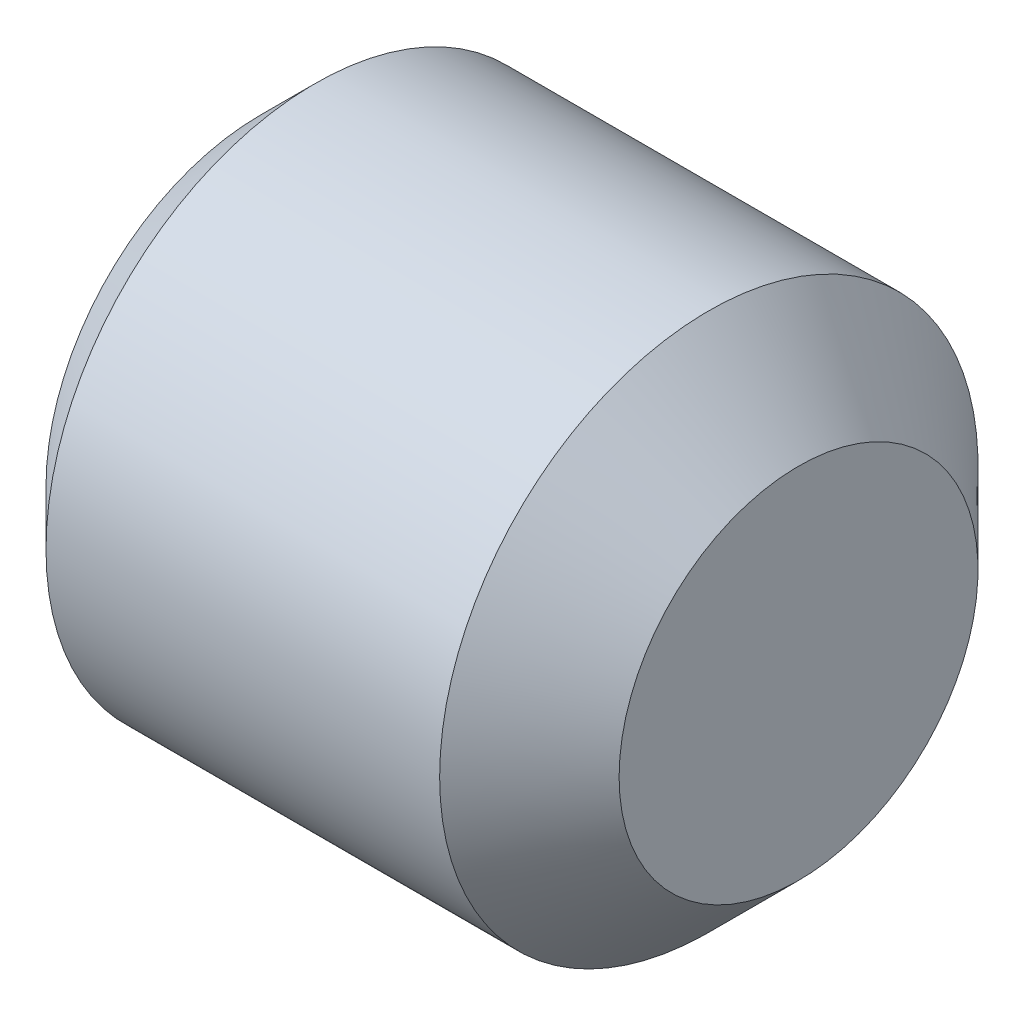
SolidWorks part; units mm, degrees
ref_plane "Front Plane" through (0, 0, 0) normal (0, 0, 1) x (1, 0, 0)
ref_plane "Top Plane" through (0, 0, 0) normal (0, 1, 0) x (1, 0, 0)
ref_plane "Right Plane" through (0, 0, 0) normal (1, 0, 0) x (0, 0, -1)
ref_plane "Plane1" through (0, 0, 0) normal (0, 0, 1) x (1, 0, 0)
sketch "Sketch1" plane through (0, 0, 0) normal (0, 0, 1) x (1, 0, 0)
  line L0 (-3, 0) -> (-3, 1.1935)
  line L1 (-3, 1.1935) -> (-2.6935, 1.5)
  line L2 (-2.6935, 1.5) -> (-0.5, 1.5)
  line L3 (-0.5, 1.5) -> (0, 1)
  line L4 (0, 1) -> (0, 0)
  line L5 (0, 0) -> (-3, 0)
  line L6 (0, 0) -> (-3, 0) construction
revolve "Revolve1" add sketch "Sketch1" angle 360 about L6
cosmetic thread "Cosmetic Thread1" parameters "D1"=3, "D2"=2.387
ref_plane "Plane2" through (-3, 0, 0) normal (-1, 0, 0) x (0, 0, 1)
sketch "Sketch2" plane through (-3, 0, 0) normal (-1, 0, 0) x (0, 0, 1)
  line L0 (-0.433, -0.75) -> (0.433, -0.75)
  line L1 (0.433, -0.75) -> (0.866, 0)
  line L2 (0.866, 0) -> (0.433, 0.75)
  line L3 (0.433, 0.75) -> (-0.433, 0.75)
  line L4 (-0.433, 0.75) -> (-0.866, 0)
  line L5 (-0.866, 0) -> (-0.433, -0.75)
extrude "Cut-Extrude1" cut sketch "Sketch2" against normal blind 1.2
ref_plane "Plane3" through (0, 0, 0) normal (0, 0, 1) x (1, 0, 0)
sketch "Sketch3" plane through (0, 0, 0) normal (0, 0, 1) x (1, 0, 0)
  line L0 (-1.8, 0) -> (-1.8, 0.75)
  line L1 (-1.8, 0.75) -> (-1.367, 0)
  line L2 (-1.367, 0) -> (-1.8, 0)
  line L3 (-1.367, 0) -> (-1.8, 0) construction
revolve "Cut-Revolve1" cut sketch "Sketch3" angle 360 about L3
